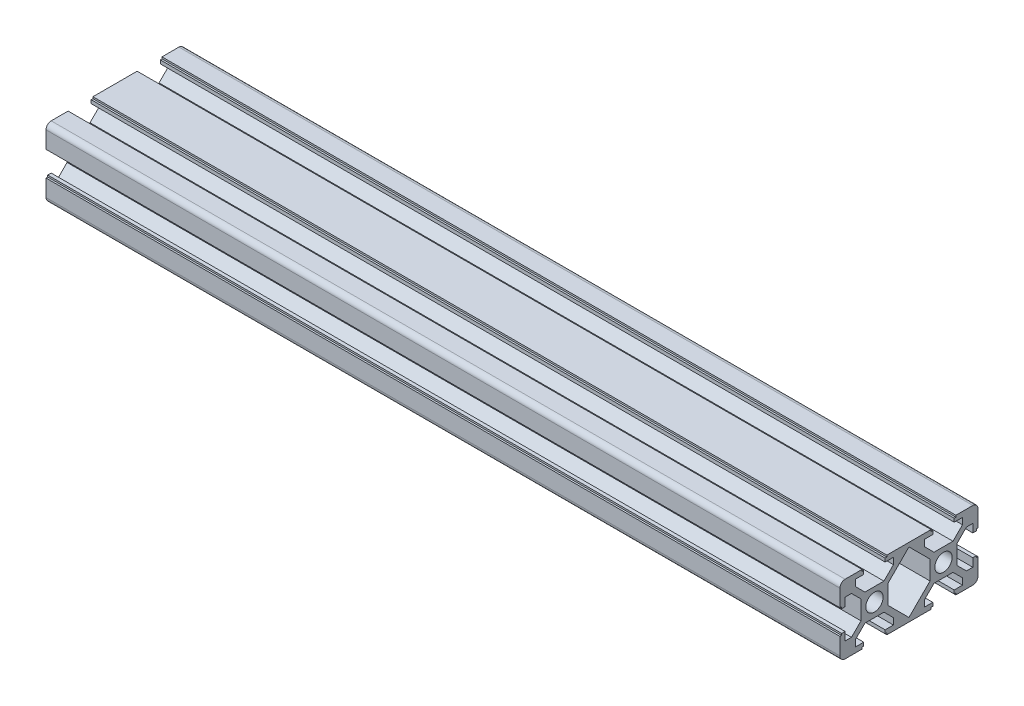
SolidWorks part; units mm, degrees
ref_plane "前视基准面" through (0, 0, 0) normal (0, 0, 1) x (1, 0, 0)
ref_plane "上视基准面" through (0, 0, 0) normal (0, 1, 0) x (1, 0, 0)
ref_plane "右视基准面" through (0, 0, 0) normal (1, 0, 0) x (0, 0, -1)
sketch "草图1" plane through (0, 0, 0) normal (0, 0, 1) x (1, 0, 0)
  line L0 (-53.3425, -1.4522) -> (176.6575, -1.4522)
other "铝型材 20X40XR1.5(2)"
ref_plane "基准面9" through (-53.3425, -1.4522, 0) normal (1, 0, 0) x (0, 1, 0)
sketch "Sketch16" plane through (-53.3425, -1.4522, 0) normal (1, 0, 0) x (0, 1, 0)
  line L0 (-3.6, 10) -> (-3.6, 9.5)
  line L1 (-3.6, 9.5) -> (-3.1, 9.5)
  line L2 (-3.1, 9.5) -> (-3.1, 8.5)
  line L3 (-3.1, 8.5) -> (-5.5, 8.5)
  line L4 (8.85, -10) -> (2.75, -3.9)
  line L5 (-10, -16.4) -> (-10, -3.6)
  line L6 (8.5, 10) -> (3.6, 10)
  line L7 (10, 8.5) -> (10, 3.6)
  line L8 (0, 14.8756) -> (0, 0) construction
  line L9 (0, 0) -> (10, 0) construction
  line L10 (-5.5, 8.5) -> (-5.5, 6.65)
  line L11 (-5.5, 6.65) -> (-2.75, 3.9)
  line L12 (-2.75, 3.9) -> (2.75, 3.9)
  line L13 (5.5, 6.65) -> (2.75, 3.9)
  line L14 (5.5, 8.5) -> (5.5, 6.65)
  line L15 (3.1, 8.5) -> (5.5, 8.5)
  line L16 (3.1, 9.5) -> (3.1, 8.5)
  line L17 (3.6, 9.5) -> (3.1, 9.5)
  line L18 (3.6, 10) -> (3.6, 9.5)
  line L19 (-3.6, 10) -> (-8.5, 10)
  line L20 (10, 3.6) -> (9.5, 3.6)
  line L21 (9.5, 3.6) -> (9.5, 3.1)
  line L22 (9.5, 3.1) -> (8.5, 3.1)
  line L23 (8.5, 3.1) -> (8.5, 5.5)
  line L24 (8.5, 5.5) -> (6.65, 5.5)
  line L25 (6.65, 5.5) -> (3.9, 2.75)
  line L26 (3.9, 2.75) -> (3.9, -2.75)
  line L27 (6.65, -5.5) -> (3.9, -2.75)
  line L28 (8.5, -5.5) -> (6.65, -5.5)
  line L29 (8.5, -3.1) -> (8.5, -5.5)
  line L30 (9.5, -3.1) -> (8.5, -3.1)
  line L31 (9.5, -3.6) -> (9.5, -3.1)
  line L32 (10, -3.6) -> (9.5, -3.6)
  line L33 (8.85, -10) -> (2.75, -16.1)
  line L34 (-8.85, -10) -> (-2.75, -16.1)
  line L35 (-8.85, -10) -> (-2.75, -3.9)
  line L39 (2.75, -3.9) -> (-2.75, -3.9)
  line L46 (-10, -3.6) -> (-9.5, -3.6)
  line L47 (-9.5, -3.6) -> (-9.5, -3.1)
  line L48 (-9.5, -3.1) -> (-8.5, -3.1)
  line L49 (-8.5, -3.1) -> (-8.5, -5.5)
  line L50 (-8.5, -5.5) -> (-6.65, -5.5)
  line L51 (-6.65, -5.5) -> (-3.9, -2.75)
  line L52 (-3.9, -2.75) -> (-3.9, 2.75)
  line L53 (-6.65, 5.5) -> (-3.9, 2.75)
  line L54 (-8.5, 5.5) -> (-6.65, 5.5)
  line L55 (-8.5, 3.1) -> (-8.5, 5.5)
  line L56 (-9.5, 3.1) -> (-8.5, 3.1)
  line L57 (-9.5, 3.6) -> (-9.5, 3.1)
  line L58 (-10, 3.6) -> (-9.5, 3.6)
  line L60 (-10, 3.6) -> (-10, 8.5)
  line L61 (10, -3.6) -> (10, -16.4)
  line L66 (-8.5, -30) -> (-3.6, -30)
  line L67 (-10, -28.5) -> (-10, -23.6)
  line L72 (-2.75, -16.1) -> (2.75, -16.1)
  line L80 (10, -16.4) -> (9.5, -16.4)
  line L81 (9.5, -16.4) -> (9.5, -16.9)
  line L82 (9.5, -16.9) -> (8.5, -16.9)
  line L83 (8.5, -16.9) -> (8.5, -14.5)
  line L84 (8.5, -14.5) -> (6.65, -14.5)
  line L85 (6.65, -14.5) -> (3.9, -17.25)
  line L86 (3.9, -17.25) -> (3.9, -22.75)
  line L87 (6.65, -25.5) -> (3.9, -22.75)
  line L88 (8.5, -25.5) -> (6.65, -25.5)
  line L89 (8.5, -23.1) -> (8.5, -25.5)
  line L90 (9.5, -23.1) -> (8.5, -23.1)
  line L91 (9.5, -23.6) -> (9.5, -23.1)
  line L92 (10, -23.6) -> (9.5, -23.6)
  line L93 (3.6, -30) -> (3.6, -29.5)
  line L94 (3.6, -29.5) -> (3.1, -29.5)
  line L95 (3.1, -29.5) -> (3.1, -28.5)
  line L96 (3.1, -28.5) -> (5.5, -28.5)
  line L97 (5.5, -28.5) -> (5.5, -26.65)
  line L98 (5.5, -26.65) -> (2.75, -23.9)
  line L99 (2.75, -23.9) -> (-2.75, -23.9)
  line L100 (-5.5, -26.65) -> (-2.75, -23.9)
  line L101 (-5.5, -28.5) -> (-5.5, -26.65)
  line L102 (-3.1, -28.5) -> (-5.5, -28.5)
  line L103 (-3.1, -29.5) -> (-3.1, -28.5)
  line L104 (-3.6, -29.5) -> (-3.1, -29.5)
  line L105 (-3.6, -30) -> (-3.6, -29.5)
  line L106 (-10, -23.6) -> (-9.5, -23.6)
  line L107 (-9.5, -23.6) -> (-9.5, -23.1)
  line L108 (-9.5, -23.1) -> (-8.5, -23.1)
  line L109 (-8.5, -23.1) -> (-8.5, -25.5)
  line L110 (-8.5, -25.5) -> (-6.65, -25.5)
  line L111 (-6.65, -25.5) -> (-3.9, -22.75)
  line L112 (-3.9, -22.75) -> (-3.9, -17.25)
  line L113 (-6.65, -14.5) -> (-3.9, -17.25)
  line L114 (-8.5, -14.5) -> (-6.65, -14.5)
  line L115 (-8.5, -16.9) -> (-8.5, -14.5)
  line L116 (-9.5, -16.9) -> (-8.5, -16.9)
  line L117 (-9.5, -16.4) -> (-9.5, -16.9)
  line L118 (-10, -16.4) -> (-9.5, -16.4)
  line L119 (3.6, -30) -> (8.5, -30)
  line L121 (10, -23.6) -> (10, -28.5)
  line L122 (0, -20) -> (10, -20) construction
  line L125 (3.6, -10) -> (3.6, -9.5) [skipped]
  line L127 (3.6, -9.5) -> (3.1, -9.5) [skipped]
  line L129 (3.1, -9.5) -> (3.1, -8.5) [skipped]
  line L131 (3.1, -8.5) -> (5.5, -8.5) [skipped]
  line L133 (-3.1, -8.5) -> (-5.5, -8.5) [skipped]
  line L135 (-3.1, -9.5) -> (-3.1, -8.5) [skipped]
  line L137 (-3.6, -9.5) -> (-3.1, -9.5) [skipped]
  line L139 (-3.6, -10) -> (-3.6, -9.5) [skipped]
  line L141 (-3.6, -10) -> (-3.6, -10.5) [skipped]
  line L142 (-3.6, -10.5) -> (-3.1, -10.5) [skipped]
  line L143 (-3.1, -10.5) -> (-3.1, -11.5) [skipped]
  line L144 (-3.1, -11.5) -> (-5.5, -11.5) [skipped]
  line L145 (8.5, -10) -> (3.6, -10) [skipped]
  line L146 (3.1, -11.5) -> (5.5, -11.5) [skipped]
  line L147 (3.1, -10.5) -> (3.1, -11.5) [skipped]
  line L148 (3.6, -10.5) -> (3.1, -10.5) [skipped]
  line L149 (3.6, -10) -> (3.6, -10.5) [skipped]
  line L150 (-3.6, -10) -> (-8.5, -10) [skipped]
  line L151 (-10, -16.4) -> (-10, -11.5) [skipped]
  line L152 (10, -11.5) -> (10, -16.4) [skipped]
  line L154 (-5.5, -8.5) -> (-5.5, -6.65) [skipped]
  line L156 (5.5, -8.5) -> (5.5, -6.65) [skipped]
  line L157 (5.5, -11.5) -> (5.5, -13.35) [skipped]
  line L158 (-5.5, -11.5) -> (-5.5, -13.35) [skipped]
  line L160 (-12.2446, -13.3946) -> (-10, -11.15) [skipped]
  line L161 (13.644, -5.206) -> (10, -8.85) [skipped]
  line L163 (12.1963, -13.3463) -> (10, -11.15) [skipped]
  line L164 (-11.1344, -7.7156) -> (-10, -8.85) [skipped]
  circle A0 centre (0, 0) radius 2.5
  arc A1 (-10, 8.5) -> (-8.5, 10) centre (-8.5, 8.5) cw
  arc A2 (10, 8.5) -> (8.5, 10) centre (8.5, 8.5) ccw
  arc A3 (10, -28.5) -> (8.5, -30) centre (8.5, -28.5) cw
  arc A4 (-10, -28.5) -> (-8.5, -30) centre (-8.5, -28.5) ccw
  circle A5 centre (0, -20) radius 2.5
  arc A12 (-10, -11.5) -> (-8.5, -10) centre (-8.5, -11.5) cw [skipped]
  arc A13 (10, -11.5) -> (8.5, -10) centre (8.5, -11.5) ccw [skipped]
  point P0 (-10, 0)
  point P1 (10, 0)
  point P2 (0, 10)
  point P4 (0, 0)
  point P5 (0, -10)
  point P6 (-10, -10)
  point P7 (10, 10)
  point P8 (-10, 10)
  point P12 (-10, -10)
  point P13 (10, -10)
  point P15 (0, -10)
  point P16 (10, -10)
  point P36 (-10, 10)
  point P39 (10, 10)
  point P43 (-10, -20)
  point P44 (10, -20)
  point P62 (0, 0)
  point P88 (0, -30)
  point P89 (0, -20)
  point P90 (-10, -30)
  point P91 (10, -30)
  dimension "D1" = 11
  dimension "D2" = 20
  dimension "D3" = 6.2
  dimension "D4" = 7.2
  dimension "D5" = 6.1
  dimension "D6" = 5
  dimension "D7" = 1.5
  dimension "D8" = 45
  dimension "D14" = 20
  dimension "D15" = 1.5
  dimension "D9" = 0.5
  dimension "D10" = 1
  dimension "D11" = 5.5
  dimension "D12" = 10
  dimension "D13" = 40
  dimension "D16" = 45
  dimension "D17" = 45
  dimension "D18" = 45
  dimension "D19" = 6.2
